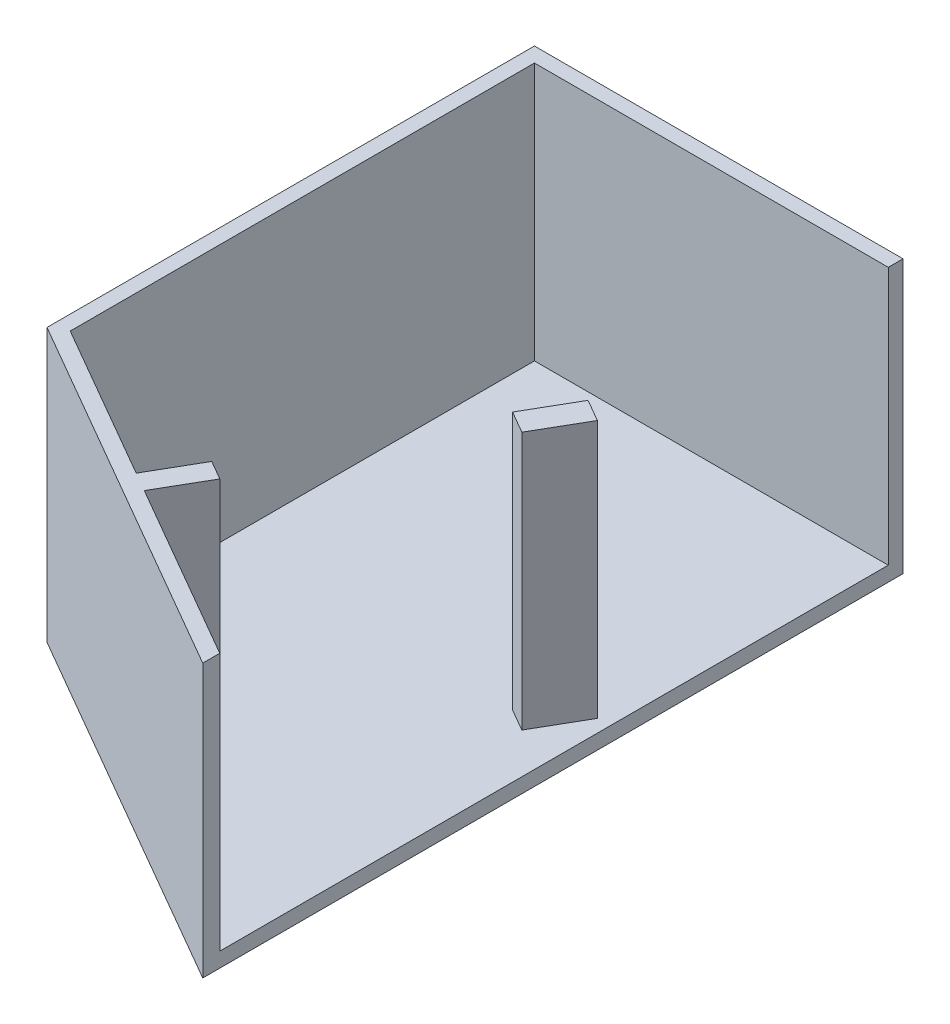
SolidWorks part; units mm, degrees
ref_plane "前视基准面" through (0, 0, 0) normal (0, 0, 1) x (1, 0, 0)
ref_plane "上视基准面" through (0, 0, 0) normal (0, 1, 0) x (1, 0, 0)
ref_plane "右视基准面" through (0, 0, 0) normal (1, 0, 0) x (0, 0, -1)
sketch "草图1" plane through (0, 0, 0) normal (0, 1, 0) x (1, 0, 0)
  line L0 (0, 0) -> (100, 0)
  line L1 (100, 0) -> (100, -190)
  line L2 (100, -190) -> (0, -132.265)
  line L3 (0, -132.265) -> (0, 0)
  dimension "D1" = 60
  dimension "D2" = 100
  dimension "D3" = 190
extrude "凸台-拉伸1" add sketch "草图1" along normal blind 74
shell "抽壳1" thickness 4
sketch "草图2" plane through (0, 4, 0) normal (0, 1, 0) x (1, 0, 0)
  line L0 (55, -159.4004) -> (100, -81.4581) construction
  line L1 (4, -129.9556) -> (100, -185.3812) construction
  line L2 (100, -185.3812) -> (100, -4) construction
  line L3 (100, -81.4581) -> (96.5359, -79.4581) construction
  line L4 (96.5359, -79.4581) -> (89.0359, -92.4485)
  line L5 (89.0359, -92.4485) -> (83.0359, -88.9844)
  line L6 (83.0359, -88.9844) -> (90.5359, -75.994)
  line L7 (90.5359, -75.994) -> (96.5359, -79.4581)
  line L8 (51.5359, -157.4004) -> (59.0359, -144.4101)
  line L9 (59.0359, -144.4101) -> (53.8397, -141.4101)
  line L10 (53.8397, -141.4101) -> (46.3397, -154.4004)
  line L11 (46.3397, -154.4004) -> (51.5359, -157.4004)
  dimension "D1" = 90
  dimension "D2" = 6
  dimension "D3" = 6
  dimension "D4" = 4
  dimension "D5" = 4
  dimension "D6" = 15
  dimension "D7" = 15
extrude "凸台-拉伸2" add sketch "草图2" along normal blind 70
